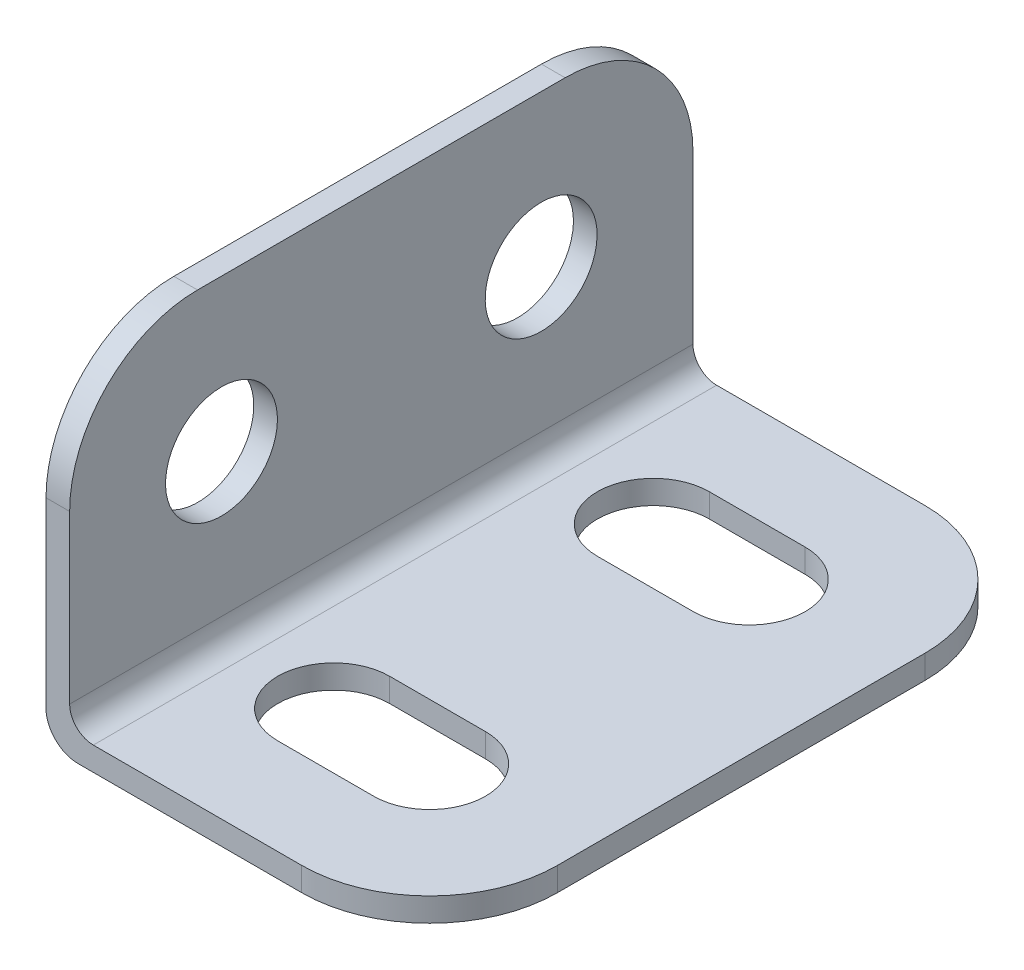
SolidWorks part; units mm, degrees
ref_plane "Front Plane" through (0, 0, 0) normal (0, 0, 1) x (1, 0, 0)
ref_plane "Top Plane" through (0, 0, 0) normal (0, 1, 0) x (1, 0, 0)
ref_plane "Right Plane" through (0, 0, 0) normal (1, 0, 0) x (0, 0, -1)
ref_plane "Plane1"
sketch "Sketch1" plane through (0, 0, 0) normal (0, 0, 1) x (1, 0, 0)
  line L0 (0, 13.589) -> (0, 1.27)
  line L1 (1.27, 0) -> (15.24, 0)
  line L2 (15.24, 0) -> (15.24, 0.9398)
  line L3 (15.24, 0.9398) -> (1.8796, 0.9398)
  line L4 (0.9398, 1.8796) -> (0.9398, 13.589)
  line L5 (0.9398, 13.589) -> (0, 13.589)
  arc A0 (0, 1.27) -> (1.27, 0) centre (1.27, 1.27) ccw
  arc A1 (0.9398, 1.8796) -> (1.8796, 0.9398) centre (1.8796, 1.8796) ccw
  dimension "D5" = 1.27
  dimension "D6" = 0.9398
  dimension "D1" = 0.9398
  dimension "D2" = 0.9398
  dimension "D3" = 15.24
  dimension "D4" = 13.589
extrude "Angle Bracket" add sketch "Sketch1" against normal blind 24.765
fillet "Corners" radius 5.08 4 edges at (0.4699, 13.589, -24.765) (15.24, 0.4699, -24.765) (15.24, 0.4699, 0) (0.4699, 13.589, 0)
sketch "Sketch2" plane through (0.9398, 0, 0) normal (1, 0, 0) x (0, 0, -1)
  circle A0 centre (6.0325, 7.5565) radius 2.2225
  circle A1 centre (18.7325, 7.5565) radius 2.2225
  dimension "D1" = 4.445
extrude "Holes" cut sketch "Sketch2" against normal through all contours A0 | A1
sketch "Sketch3" plane through (0, 0.9398, 0) normal (0, 1, 0) x (-1, 0, 0)
  line L0 (-5.3975, -3.81) -> (-9.2075, -3.81)
  line L1 (-9.2075, -8.255) -> (-5.3975, -8.255)
  line L2 (-5.3975, -16.51) -> (-9.2075, -16.51)
  line L3 (-9.2075, -20.955) -> (-5.3975, -20.955)
  arc A0 (-9.2075, -3.81) -> (-9.2075, -8.255) centre (-9.2075, -6.0325) ccw
  arc A1 (-5.3975, -8.255) -> (-5.3975, -3.81) centre (-5.3975, -6.0325) ccw
  arc A2 (-9.2075, -16.51) -> (-9.2075, -20.955) centre (-9.2075, -18.7325) ccw
  arc A3 (-5.3975, -20.955) -> (-5.3975, -16.51) centre (-5.3975, -18.7325) ccw
  dimension "D1" = 4.445
extrude "Slots" cut sketch "Sketch3" against normal through all
